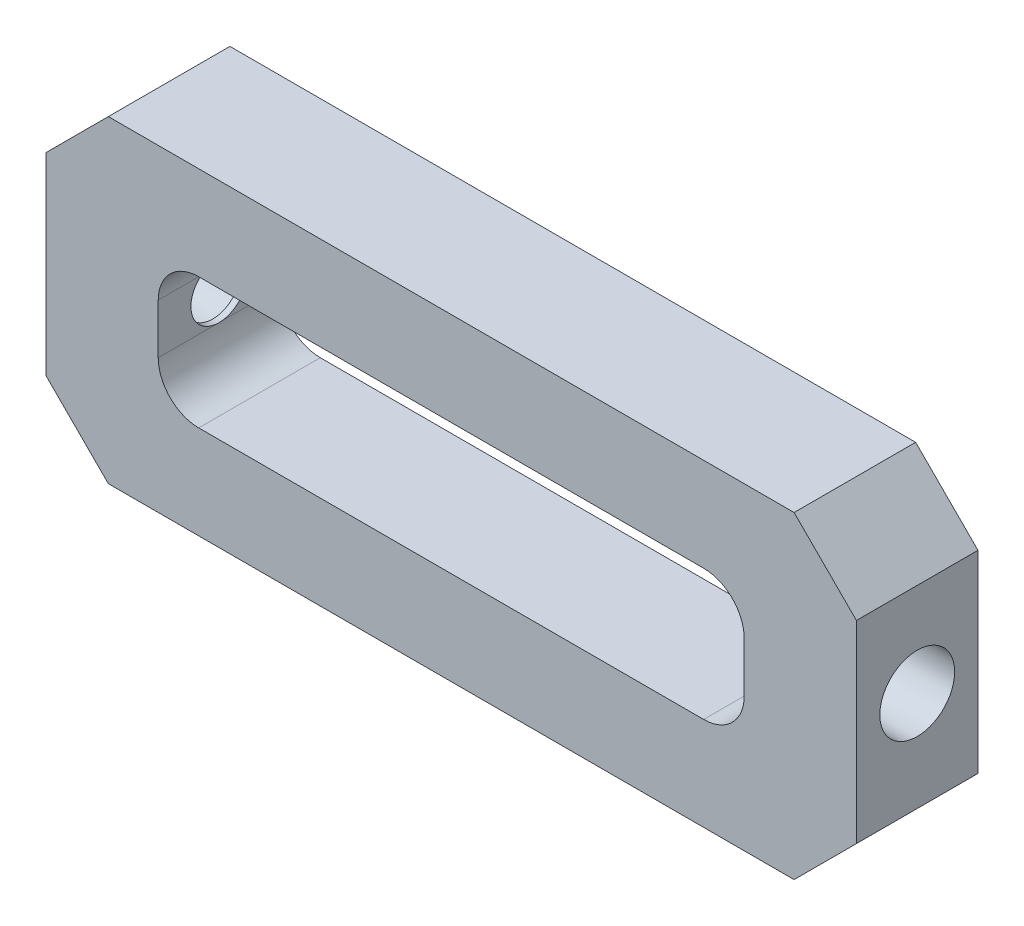
SolidWorks part; units mm, degrees
ref_plane "Front Plane" through (0, 0, 0) normal (0, 0, 1) x (1, 0, 0)
ref_plane "Top Plane" through (0, 0, 0) normal (0, 1, 0) x (1, 0, 0)
ref_plane "Right Plane" through (0, 0, 0) normal (1, 0, 0) x (0, 0, -1)
sketch "Model" plane through (0, 0, 0) normal (0, 0, 1) x (1, 0, 0)
  line L0 (0, 41) -> (0, 10)
  line L1 (10, 0) -> (120, 0)
  line L2 (0, 10) -> (10, 0)
  line L3 (0, 41) -> (10, 51)
  line L4 (10, 51) -> (120, 51)
  line L5 (24.5, 15) -> (105.5, 15)
  line L6 (18, 29.5) -> (18, 21.5)
  line L7 (24.5, 36) -> (105.5, 36)
  line L8 (112, 29.5) -> (112, 21.5)
  line L9 (130, 41) -> (120, 51)
  line L10 (130, 10) -> (120, 0)
  line L11 (130, 41) -> (130, 10)
  arc A0 (18, 21.5) -> (24.5, 15) centre (24.5, 21.5) ccw
  arc A1 (24.5, 36) -> (18, 29.5) centre (24.5, 29.5) ccw
  arc A2 (112, 29.5) -> (105.5, 36) centre (105.5, 29.5) ccw
  arc A3 (105.5, 15) -> (112, 21.5) centre (105.5, 21.5) ccw
  point P20 (112, 25.5)
  point P21 (65, 15)
  point P22 (18, 25.5)
  point P23 (65, 36)
  point P24 (65, 51)
  point P25 (65, 0)
extrude "Boss-Extrude1" add sketch "Model" along normal blind 19.5
sketch "Sketch2" plane through (0, 0, 0) normal (-1, 0, 0) x (0, 0, 1)
  line L0 (0, 41) -> (0, 10) construction
  line L1 (19.5, 41) -> (0, 41) construction
  circle A0 centre (9.75, 26) radius 8.5
  dimension "D1" = 17
  dimension "D2" = 9.75
  dimension "D3" = 15
extrude "Cut-Extrude2" cut sketch "Sketch2" against normal blind 7
sketch "Sketch3" plane through (0, 0, 0) normal (-1, 0, 0) x (0, 0, 1)
  circle A0 centre (9.75, 26) radius 4.5
  dimension "D1" = 9
extrude "Cut-Extrude3" cut sketch "Sketch3" against normal through all
sketch "Sketch5" plane through (7, 0, 0) normal (-1, 0, 0) x (0, 0, 1)
  circle A0 centre (9.75, 26) radius 6
  dimension "D1" = 12
extrude "Cut-Extrude4" cut sketch "Sketch5" against normal blind 10
sketch "Sketch6" plane through (130, 0, 0) normal (1, 0, 0) x (0, 0, -1)
  circle A0 centre (-9.75, 26) radius 6
  circle A1 centre (-9.75, 26) radius 4.5 construction
  dimension "D2" = 12
  dimension "D1" = 0
extrude "Cut-Extrude5" cut sketch "Sketch6" against normal blind 10
